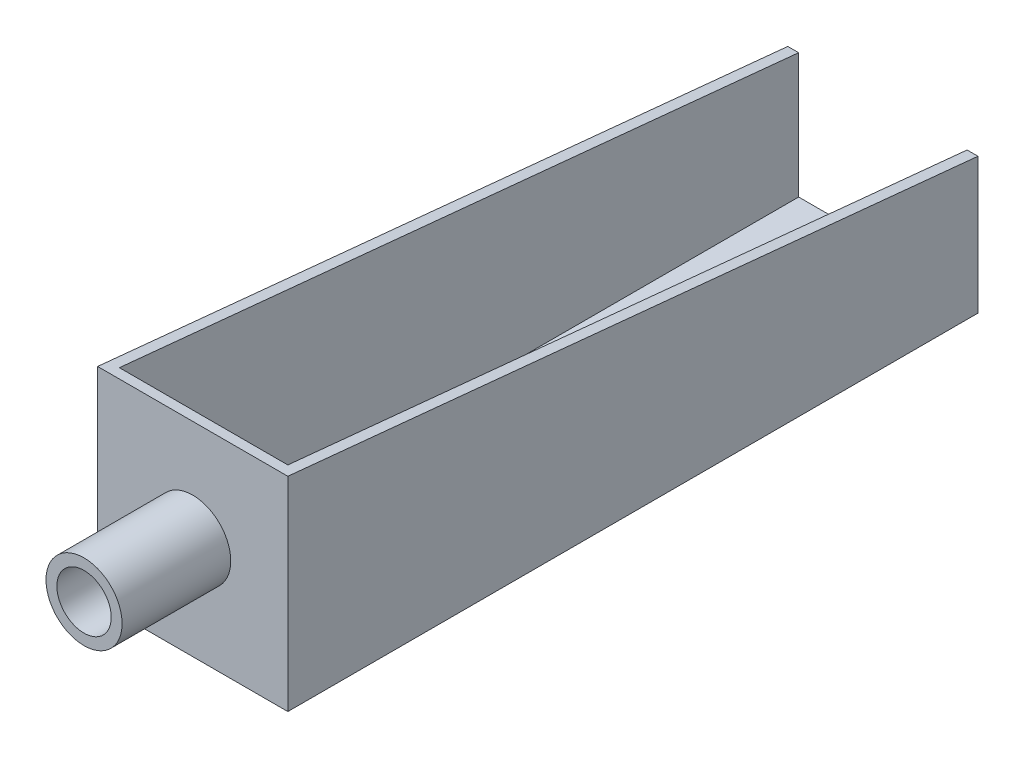
SolidWorks part; units mm, degrees
ref_plane "前视基准面" through (0, 0, 0) normal (0, 0, 1) x (1, 0, 0)
ref_plane "上视基准面" through (0, 0, 0) normal (0, 1, 0) x (1, 0, 0)
ref_plane "右视基准面" through (0, 0, 0) normal (1, 0, 0) x (0, 0, -1)
sketch "草图1" plane through (0, 0, 0) normal (0, 0, 1) x (1, 0, 0)
  line L1 (-35, -37.5) -> (35, -37.5)
  line L2 (-35, -37.5) -> (-35, 37.5)
  line L3 (-35, 37.5) -> (35, 37.5)
  line L4 (35, -37.5) -> (35, 37.5)
  line L5 (-35, -37.5) -> (35, 37.5) construction
  line L6 (-35, 37.5) -> (35, -37.5) construction
  point P0 (0, 0)
  dimension "D1" = 70
  dimension "D2" = 75
extrude "凸台-拉伸1" add sketch "草图1" along normal blind 4
sketch "草图2" plane through (0, 0, 0) normal (0, 0, -1) x (-1, 0, 0)
  line L0 (35, 37.5) -> (35, -37.5) construction
  line L1 (35, -37.5) -> (-35, -37.5) construction
  line L2 (-35, -37.5) -> (-35, 37.5) construction
  line L3 (35, 37.5) -> (35, -37.5)
  line L4 (35, -37.5) -> (-35, -37.5)
  line L5 (-35, -37.5) -> (-35, 37.5)
  line L6 (31, 37.5) -> (31, -33.5)
  line L7 (31, -33.5) -> (-31, -33.5)
  line L8 (-31, -33.5) -> (-31, 37.5)
  line L9 (-35, 37.5) -> (-31, 37.5)
  line L10 (31, 37.5) -> (35, 37.5)
  dimension "D1" = 4
extrude "凸台-拉伸2" add sketch "草图2" along normal blind 250
sketch "草图3" plane through (-35, 0, 0) normal (-1, 0, 0) x (0, 0, 1)
  line L0 (4, 37.5) -> (-250, 37.5) construction
  line L1 (-250, -37.5) -> (-250, 37.5) construction
  line L2 (4, 37.5) -> (-250, 37.5)
  line L3 (-250, 12.5) -> (-250, 37.5)
  line L4 (-250, 12.5) -> (4, 37.5)
  dimension "D1" = 50
extrude "切除-拉伸1" cut sketch "草图3" against normal through all
sketch "草图4" plane through (0, 0, 4) normal (0, 0, 1) x (1, 0, 0)
  circle A0 centre (0, 0) radius 14
  circle A1 centre (0, 0) radius 10
  dimension "D1" = 28
  dimension "D2" = 4
extrude "凸台-拉伸3" add sketch "草图4" along normal blind 40
